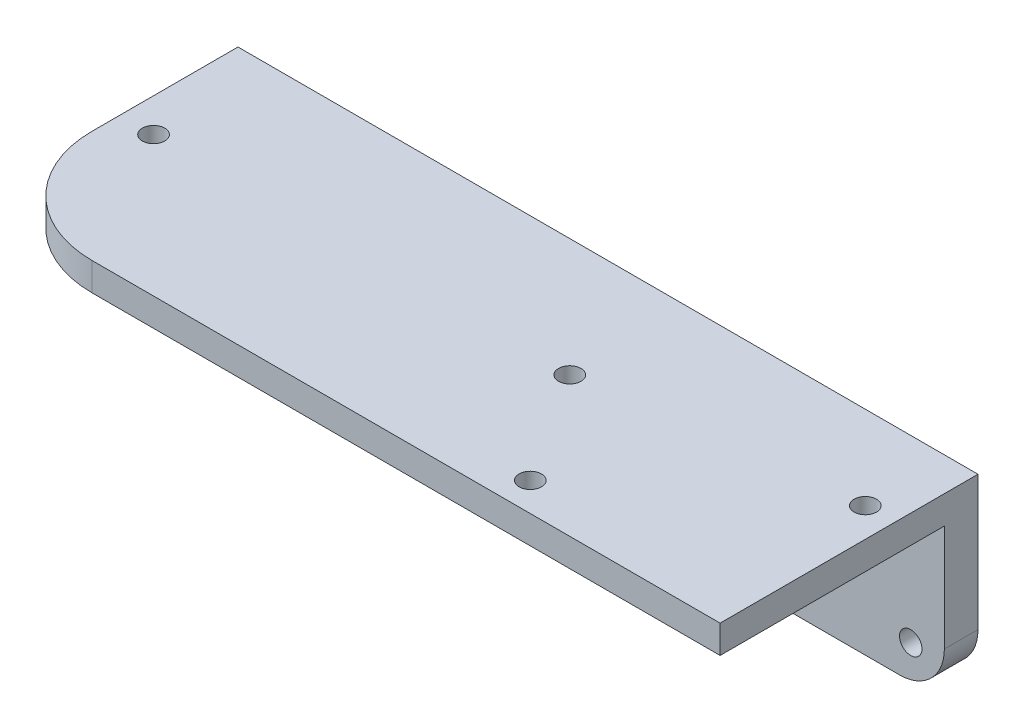
SolidWorks part; units mm, degrees
ref_plane "Plano frontal" through (0, 0, 0) normal (0, 0, 1) x (1, 0, 0)
ref_plane "Plano superior" through (0, 0, 0) normal (0, 1, 0) x (1, 0, 0)
ref_plane "Plano direito" through (0, 0, 0) normal (1, 0, 0) x (0, 0, -1)
sketch "Esboço21" plane through (0, 0, 0) normal (0, 0, 1) x (1, 0, 0)
  line L1 (-33, -8) -> (33, -8)
  line L2 (-33, -8) -> (-33, 8)
  line L3 (-33, 8) -> (33, 8)
  line L4 (33, -8) -> (33, 8)
  line L5 (-33, -8) -> (33, 8) construction
  line L6 (-33, 8) -> (33, -8) construction
  point P0 (0, 0)
  dimension "D1" = 66
  dimension "D2" = 16
extrude "Ressalto-extrusão1" add sketch "Esboço21" along normal blind 3
sketch "Esboço22" plane through (0, 0, 3) normal (0, 0, 1) x (1, 0, 0)
  line L0 (33, -8) -> (33, 8) construction
  line L1 (-33, 8) -> (33, 8)
  line L2 (-33, 8) -> (-33, 5.5)
  line L3 (-33, 5.5) -> (33, 5.5)
  line L4 (33, 8) -> (33, 5.5)
  dimension "D1" = 2.5
extrude "Ressalto-extrusão2" add sketch "Esboço22" along normal blind 20
sketch "Esboço23" plane through (0, 5.5, 0) normal (0, -1, 0) x (1, 0, 0)
  line L0 (-33, 3) -> (-30, 3) construction
  line L1 (-33, 3) -> (33, 3) construction
  line L2 (-30, 3) -> (-30, 10.53) construction
  line L3 (-30, 10.53) -> (7.12, 10.53) construction
  line L4 (33, 3) -> (30.4, 3) construction
  line L5 (30.4, 3) -> (30.4, 7.45) construction
  line L6 (30.4, 7.45) -> (13.51, 7.45) construction
  line L7 (13.51, 7.45) -> (13.51, 20.44) construction
  circle A0 centre (-30, 10.53) radius 1
  circle A1 centre (7.12, 10.53) radius 1
  circle A2 centre (30.4, 7.45) radius 1
  circle A3 centre (13.51, 20.44) radius 1
  dimension "D2" = 2
  dimension "D5" = 2
  dimension "D8" = 2
  dimension "D11" = 2
  dimension "D1" = 3
  dimension "D3" = 7.53
  dimension "D4" = 37.12
  dimension "D6" = 4.45
  dimension "D7" = 2.6
  dimension "D9" = 16.89
  dimension "D10" = 12.99
extrude "Corte-extrusão9" cut sketch "Esboço23" against normal through all
sketch "Esboço24" plane through (0, 0, 3) normal (0, 0, 1) x (1, 0, 0)
  line L0 (-33, 5.5) -> (-33, -8) construction
  line L2 (-33, -8) -> (33, -8) construction
  line L4 (-16.27, -5) -> (-8.27, -5)
  line L5 (-16.27, -5) -> (-16.27, 5)
  line L6 (-16.27, 5) -> (-8.27, 5)
  line L7 (-8.27, -5) -> (-8.27, 5)
  circle A0 centre (-30, -5) radius 1
  dimension "D6" = 2
  dimension "D1" = 3
  dimension "D2" = 3
  dimension "D3" = 10
  dimension "D4" = 8
  dimension "D5" = 3
extrude "Corte-extrusão10" cut sketch "Esboço24" against normal through all
fillet "Filete1" radius 10 1 edges at (-33, 6.75, 23)
fillet "Filete2" radius 4 2 edges at (33, -8, 1.5) (-33, -8, 1.5)
mirror "Espelhar1" about plane through (0, 0, 0) normal (1, 0, 0) of "Corte-extrusão10"
fillet "Filete3" radius 1 8 edges at (16.27, -5, 1.5) (16.27, 5, 1.5) (8.27, -5, 1.5) (8.27, 5, 1.5) (-8.27, -5, 1.5) (-16.27, -5, 1.5) (-8.27, 5, 1.5) (-16.27, 5, 1.5)
